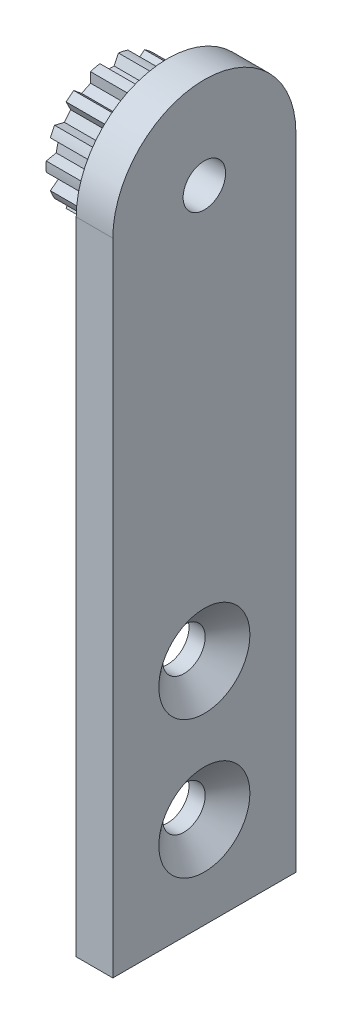
SolidWorks part; units mm, degrees
ref_plane "Front Plane" through (0, 0, 0) normal (0, 0, 1) x (1, 0, 0)
ref_plane "Top Plane" through (0, 0, 0) normal (0, 1, 0) x (1, 0, 0)
ref_plane "Right Plane" through (0, 0, 0) normal (1, 0, 0) x (0, 0, -1)
sketch "Sketch2" plane through (0, 0, 0) normal (1, 0, 0) x (0, 0, -1)
  line L3 (0, 0) -> (0, 3.7084) construction
  line L6 (0, -4.2164) -> (0, -4.5339) construction
  line L7 (-0.5715, 4.1775) -> (-0.3452, 3.6923)
  line L8 (0.5715, 4.1775) -> (0.3452, 3.6923)
  line L9 (-0.5715, 4.1775) -> (-0.6416, 4.3278)
  line L10 (0.5715, 4.1775) -> (0.6416, 4.3278)
  line L12 (-0.3452, 3.6923) -> (0.3452, 3.6923)
  line L14 (0, 4.2164) -> (0, 4.5339) construction
  line L15 (0, 0) -> (0, -1.143) construction
  circle A0 centre (0, 0) radius 4.5339 construction
  circle A1 centre (0, 0) radius 3.7084 construction
  circle A2 centre (0, 0) radius 4.2164 construction
  arc A7 (0.6416, 4.3278) -> (-0.6416, 4.3278) centre (0, 0) ccw
  point P5 (0, 4.3751)
  dimension "D3" = 0.3175
  dimension "D1" = 50
sketch "Sketch1" plane through (0, 0, 0) normal (0, 0, 1) x (1, 0, 0)
  line L0 (-5.5626, 0) -> (5.5626, 0) construction
  line L1 (-5.5626, 1.5875) -> (5.5626, 1.5875)
  line L2 (-5.5626, 1.5875) -> (-5.5626, 6.731)
  line L3 (-5.5626, 6.731) -> (-0.5969, 6.731)
  line L4 (-0.5969, 6.731) -> (0.4572, 5.6769)
  line L5 (0.4572, 5.6769) -> (0.4572, 4.5339)
  line L6 (0.4572, 4.5339) -> (4.5212, 4.5339)
  line L7 (4.5212, 4.5339) -> (4.5212, 5.1054)
  line L8 (4.5212, 4.5339) -> (5.5626, 4.5339) construction
  line L9 (5.0419, 6.731) -> (5.5626, 6.731)
  line L10 (5.5626, 6.731) -> (5.5626, 1.5875)
  line L11 (5.0419, 4.5339) -> (5.0419, 6.731) construction
  line L12 (-3.0797, 6.731) -> (-3.0797, 1.5875) construction
  arc A0 (4.5212, 5.1054) -> (5.0419, 6.731) centre (7.3191, 5.1054) cw
  dimension "Bore Size" = 3.175
  dimension "Overall Width" = 11.1252
  dimension "Inside Width" = 4.064
  dimension "Outside Width" = 5.1054
  dimension "Hub Dia" = 13.462
  dimension "OD" = 13.462
  dimension "D1" = 45
  dimension "D2" = 9.0678
  dimension "D3" = 1.143
  dimension "D4" = 0.5715
revolve "Revolve1" add sketch "Sketch1" angle 360 mid plane about L0
sketch "Sketch4" plane through (0.4572, 0, 0) normal (1, 0, 0) x (0, 0, -1)
  circle A0 centre (0, 0) radius 4.3751
  circle A1 centre (0, 0) radius 4.5339 construction
  circle A2 centre (0, 0) radius 4.5339
extrude "Cut-Extrude2" cut sketch "Sketch4" along normal up to surface (4.064 mm away) up to face at (4.5212, 0, 4.5339)
sketch "Sketch3" plane through (0.4572, 0, 0) normal (1, 0, 0) x (0, 0, -1)
  line L2 (-0.5715, 4.1775) -> (-0.3452, 3.6923) construction
  line L3 (-0.3452, 3.6923) -> (0.3452, 3.6923) construction
  line L4 (0.5715, 4.1775) -> (0.3452, 3.6923) construction
  line L5 (-0.6416, 4.3278) -> (-0.3452, 3.6923)
  line L6 (-0.3452, 3.6923) -> (0.3452, 3.6923)
  line L7 (0.6416, 4.3278) -> (0.3452, 3.6923)
  arc A1 (0.6416, 4.3278) -> (-0.6416, 4.3278) centre (0, 0) ccw construction
  arc A2 (0.6416, 4.3278) -> (-0.6416, 4.3278) centre (0, 0) ccw
extrude "Cut-Extrude1" cut sketch "Sketch3" along normal up to surface (4.064 mm away)
pattern_circular "CirPattern1" count 14 over 360 about axis through (0, 0, 0) along (1, 0, 0) of "Cut-Extrude1"
sketch "Sketch5" plane through (0, 0, 0) normal (0, 0, 1) x (1, 0, 0)
  line L1 (4.5212, 5.1054) -> (4.5212, -5.1054) construction
  point P0 (4.5212, 0)
sketch "Sketch6" plane through (0, 0, 0) normal (0, 1, 0) x (1, 0, 0)
  line L0 (-5.5626, 0) -> (-4.1402, 0) construction
  line L1 (-5.5626, 6.731) -> (-5.5626, -6.731) construction
  line L2 (0.4572, 0) -> (-0.9652, 0) construction
  line L3 (0.4572, -0.3452) -> (0.4572, 0.3452) construction
  circle A0 centre (-2.5527, 0) radius 1.5875
  dimension "D1" = 3.175
extrude "Cut-Extrude3" cut sketch "Sketch6" along normal through all
sketch "Sketch7" plane through (0, 0, 0) normal (0, 0, 1) x (1, 0, 0)
  line L0 (-3.7211, 6.731) -> (-2.5527, 6.731)
  line L1 (-3.9751, 6.477) -> (-3.9751, 2.2225)
  line L2 (-3.9751, 2.2225) -> (-3.7211, 1.9685)
  line L3 (-3.7211, 1.9685) -> (-2.5527, 1.9685)
  line L4 (-2.5527, 1.9685) -> (-2.5527, 6.731) construction
  line L6 (-3.9751, 6.477) -> (-3.7211, 6.731)
  line L7 (-5.5626, 6.731) -> (-0.5969, 6.731) construction
  line L8 (-2.5527, 6.731) -> (-2.5527, 1.9685)
  point P0 (-3.9751, 6.731)
  point P4 (-3.9751, 1.9685)
  dimension "D1" = 2.8448
  dimension "D2" = 0.381
revolve "Revolve2" add sketch "Sketch7" angle 360 mid plane about L4
sketch "Sketch8" plane through (0, 6.731, 0) normal (0, 1, 0) x (1, 0, 0)
  line L1 (-2.5527, 0.8212) -> (-3.2639, 0.4106)
  line L2 (-3.2639, 0.4106) -> (-3.2639, -0.4106)
  line L3 (-3.2639, -0.4106) -> (-2.5527, -0.8212)
  line L4 (-2.5527, -0.8212) -> (-1.8415, -0.4106)
  line L5 (-1.8415, -0.4106) -> (-1.8415, 0.4106)
  line L6 (-1.8415, 0.4106) -> (-2.5527, 0.8212)
  circle A0 centre (-2.5527, 0) radius 0.7112 construction
  dimension "D1" = 1.4224
extrude "Cut-Extrude4" cut sketch "Sketch8" against normal blind 1.016
pattern_circular "CirPattern2" [suppressed] count 2 over 90
pattern_circular "CirPattern3" [suppressed] count 2 over 90
sketch "Sketch11" plane through (4.5212, 0, 0) normal (-1, 0, 0) x (0, 0, 1)
  circle A1 centre (0, 0) radius 6.731
  circle A4 centre (0, 0) radius 6.731 construction
extrude "Cut-Extrude6" cut sketch "Sketch11" against normal blind 2.54
sketch "Sketch13" plane through (0.4572, 0, 0) normal (1, 0, 0) x (0, 0, -1)
  circle A0 centre (0, 0) radius 9.525
  dimension "D1" = 19.05
extrude "Cut-Extrude7" cut sketch "Sketch13" against normal through all
ref_plane "Plane1" through (2.4892, 0, 0) normal (-1, 0, 0) x (0, 0, 1)
sketch "Sketch17" plane through (0.4572, 0, 0) normal (-1, 0, 0) x (0, 0, 1)
  circle A0 centre (0, 0) radius 1.4732
  circle A1 centre (0, 0) radius 1.5875
  circle A2 centre (0, 0) radius 1.5875 construction
  dimension "D1" = 2.9464
extrude "Boss-Extrude2" add sketch "Sketch17" against normal up to surface (4.064 mm away) up to face at (4.5212, 0, 0)
sketch "Sketch12" plane through (4.5212, 0, 0) normal (1, 0, 0) x (0, 0, -1)
  line L0 (6.35, 0) -> (6.35, -44.45)
  line L1 (6.35, -44.45) -> (-6.35, -44.45)
  line L2 (-6.35, -44.45) -> (-6.35, 0)
  arc A0 (-6.35, 0) -> (6.35, 0) centre (0, 0) cw
  circle A2 centre (0, 0) radius 1.4732 construction
  circle A3 centre (0, 0) radius 1.4732
  dimension "D1" = 6.35
  dimension "D2" = 44.45
extrude "Boss-Extrude1" add sketch "Sketch12" along normal blind 2.54
mirror "Mirror1" [suppressed] about plane through (2.4892, 0, 0) normal (-1, 0, 0)
sketch "Sketch14" plane through (7.0612, 0, 0) normal (1, 0, 0) x (0, 0, -1)
  line L0 (0, 0) -> (0, -28.575)
  line L1 (0, -28.575) -> (0, -38.1)
  dimension "D1" = 28.575
  dimension "D2" = 9.525
hole_wizard "CSK for #4 Flat Head Machine Screw (100)1" positions "Sketch15" profile "Sketch16" countersink size "#4" standard "ANSI Inch" end condition through all
sketch "Sketch15" plane through (7.0612, 0, 0) normal (1, 0, 0) x (0, 0, -1)
  point P0 (0, -28.575)
  point P1 (0, -38.1)
sketch "Sketch16" plane through (7.0612, -28.575, 0) normal (0, 1, 0) x (0, 0, -1)
  line L0 (0, 0) -> (0, 6.604)
  line L1 (0, 6.604) -> (1.4732, 6.604)
  line L2 (1.4732, 6.604) -> (1.4732, 1.4156)
  line L3 (1.4732, 1.4156) -> (3.1602, 0)
  line L5 (3.1602, 0) -> (0, 0)
  line L6 (-1.4732, 1.4156) -> (-3.1602, 0) construction
  line L11 (0, -6.35) -> (0, 107.95) construction
  dimension "Thru Hole Dia." = 2.9464
  dimension "Thru Hole Depth" = 6.604
  dimension "Near C'Sink Dia." = 6.3204
  dimension "Near C'Sink Angle" = 100
equation "\"D3@Sketch2\" = (\"hs@Sketch2\"-\"ht@Sketch2\")/2"
equation "\"D2@Sketch1\" = \"PD@Sketch2\""
equation "\"D3@Sketch1\" = \"hs@Sketch2\""
equation "\"D4@Sketch1\" = \"D3@Sketch1\"/2"
